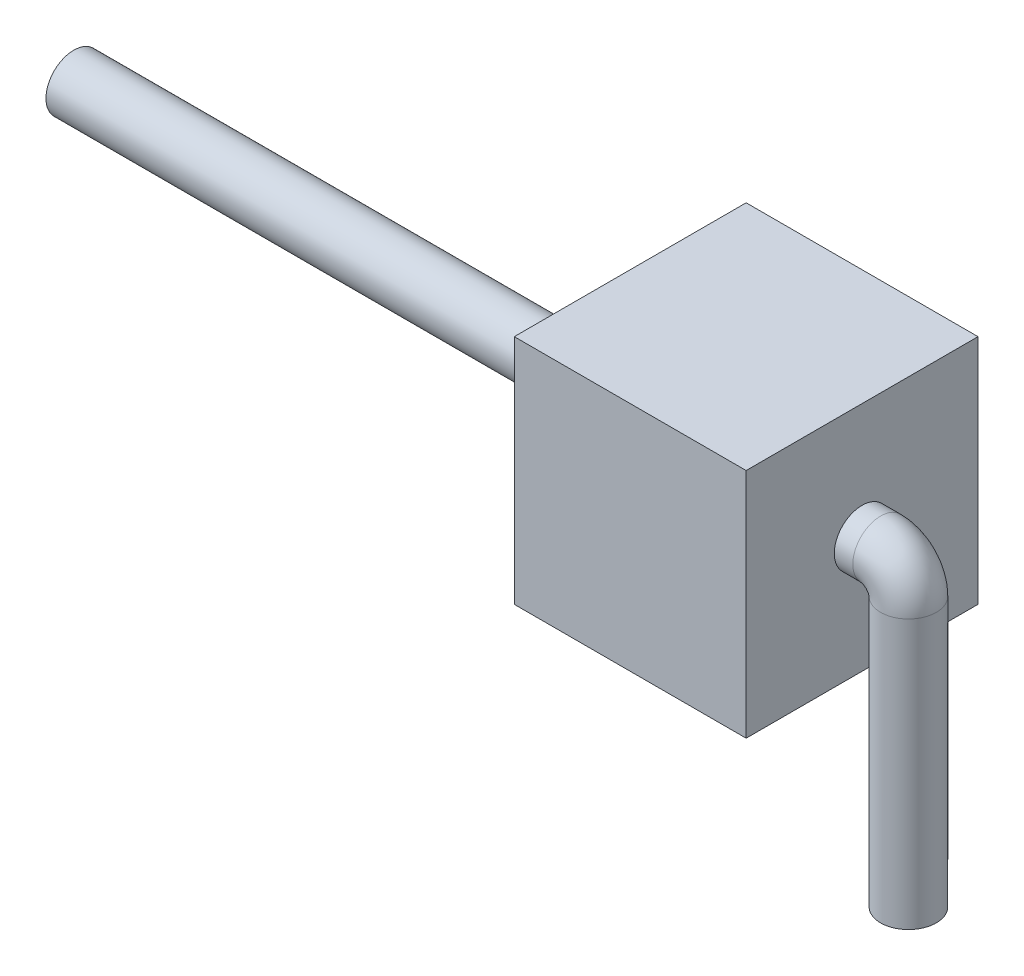
SolidWorks part; units mm, degrees
ref_plane "Спереди" through (0, 0, 0) normal (0, 0, 1) x (1, 0, 0)
ref_plane "Сверху" through (0, 0, 0) normal (0, 1, 0) x (1, 0, 0)
ref_plane "Справа" through (0, 0, 0) normal (1, 0, 0) x (0, 0, -1)
sketch "Эскиз1" plane through (0, 0, 0) normal (1, 0, 0) x (0, 0, -1)
  line L0 (0, 1.25) -> (0, -1.25) construction
  line L1 (-1.25, 1.25) -> (1.25, 1.25)
  line L2 (-1.25, 1.25) -> (-1.25, -1.25)
  line L3 (-1.25, -1.25) -> (1.25, -1.25)
  line L4 (1.25, 1.25) -> (1.25, -1.25)
  dimension "D1" = 2.5
  dimension "D2" = 2.5
extrude "Вытянуть1" add sketch "Эскиз1" along normal mid plane 2.5
sketch "Эскиз2" plane through (0, 0, 0) normal (0, 0, 1) x (1, 0, 0)
  line L0 (-7.25, 0) -> (1.45, 0)
  line L1 (1.75, -3.2) -> (1.75, -0.3)
  line L2 (-1.25, 1.25) -> (-1.25, -1.25) construction
  arc A0 (1.75, -0.3) -> (1.45, 0) centre (1.45, -0.3) ccw
  point P8 (1.75, 0)
  dimension "D4" = 0.3
  dimension "D1" = 9
  dimension "D2" = 3.2
  dimension "D3" = 3
ref_plane "Плоскость1" through (-7.25, 0, 0) normal (1, 0, 0) x (0, 0, -1)
sketch "Эскиз3" plane through (-7.25, 0, 0) normal (1, 0, 0) x (0, 0, -1)
  line L0 (0, 0.3) -> (0, -0.3) construction
  line L1 (-0.3, 0.3) -> (0.3, 0.3) construction
  line L2 (-0.3, 0.3) -> (-0.3, -0.3) construction
  line L3 (-0.3, -0.3) -> (0.3, -0.3) construction
  line L4 (0.3, 0.3) -> (0.3, -0.3) construction
  circle A0 centre (0, 0) radius 0.3
  dimension "D1" = 0.6
sweep "По траектории1" add profiles "Эскиз3" path "Эскиз2"
